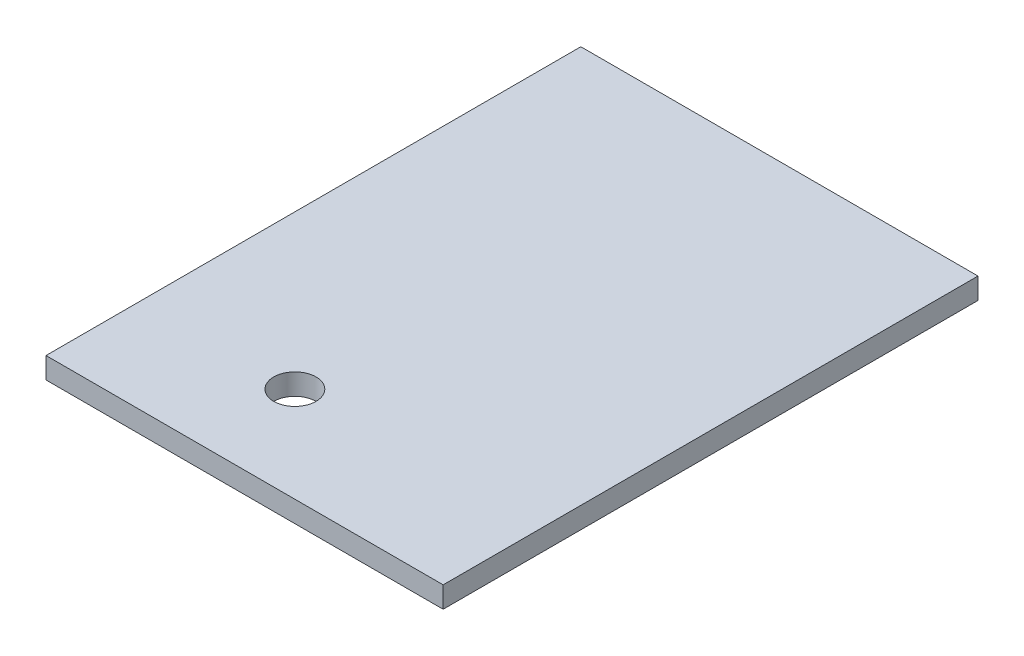
SolidWorks part; units mm, degrees
ref_plane "Front Plane" through (0, 0, 0) normal (0, 0, 1) x (1, 0, 0)
ref_plane "Top Plane" through (0, 0, 0) normal (0, 1, 0) x (1, 0, 0)
ref_plane "Right Plane" through (0, 0, 0) normal (1, 0, 0) x (0, 0, -1)
sketch "Sketch1" plane through (0, 0, 0) normal (0, 1, 0) x (1, 0, 0)
  line L1 (18.75, -25.25) -> (-18.75, -25.25)
  line L2 (18.75, -25.25) -> (18.75, 25.25)
  line L3 (18.75, 25.25) -> (-18.75, 25.25)
  line L4 (-18.75, -25.25) -> (-18.75, 25.25)
  line L5 (18.75, -25.25) -> (-18.75, 25.25) construction
  line L6 (18.75, 25.25) -> (-18.75, -25.25) construction
  point P0 (0, 0)
  dimension "D1" = 50.5
  dimension "D2" = 37.5
extrude "Boss-Extrude1" add sketch "Sketch1" along normal blind 2
sketch "Sketch2" plane through (0, 2, 0) normal (0, 1, 0) x (1, 0, 0)
  line L0 (-18.75, 25.25) -> (-18.75, -25.25) construction
  line L1 (-18.75, -25.25) -> (18.75, -25.25) construction
  circle A0 centre (-4.25, -16.25) radius 2
  dimension "D1" = 4
  dimension "D2" = 14.5
  dimension "D3" = 9
extrude "Cut-Extrude1" cut sketch "Sketch2" against normal through all
